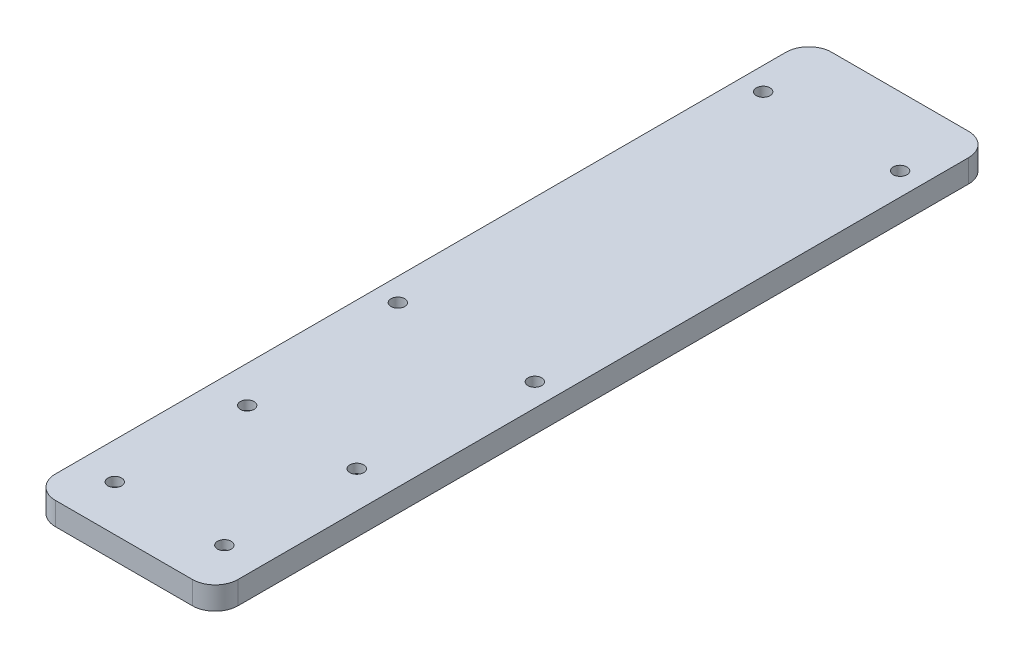
SolidWorks part; units mm, degrees
ref_plane "前视基准面" through (0, 0, 0) normal (0, 0, 1) x (1, 0, 0)
ref_plane "上视基准面" through (0, 0, 0) normal (0, 1, 0) x (1, 0, 0)
ref_plane "右视基准面" through (0, 0, 0) normal (1, 0, 0) x (0, 0, -1)
other "Configuration Table"
sketch "草图1" plane through (0, 0, 0) normal (0, 1, 0) x (1, 0, 0)
  line L0 (0, 0) -> (0, 30) construction
  line L1 (-20, 85) -> (20, 85)
  line L2 (-20, 85) -> (-20, -85)
  line L3 (-20, -85) -> (20, -85)
  line L4 (20, 85) -> (20, -85)
  line L5 (-20, 85) -> (20, -85) construction
  line L6 (-20, -85) -> (20, 85) construction
  line L7 (-15, 70) -> (15, 70) construction
  line L8 (-15, 70) -> (-15, -10) construction
  line L9 (-15, -10) -> (15, -10) construction
  line L10 (15, 70) -> (15, -10) construction
  line L11 (-15, 70) -> (15, -10) construction
  line L12 (-15, -10) -> (15, 70) construction
  line L14 (-12, -46) -> (12, -46) construction
  line L15 (-12, -46) -> (-12, -75) construction
  line L16 (-12, -75) -> (12, -75) construction
  line L17 (12, -46) -> (12, -75) construction
  line L18 (-12, -46) -> (12, -75) construction
  line L19 (-12, -75) -> (12, -46) construction
  circle A0 centre (-15, 70) radius 1.5
  circle A1 centre (15, 70) radius 1.5
  circle A2 centre (15, -10) radius 1.5
  circle A3 centre (-15, -10) radius 1.5
  circle A4 centre (12, -46) radius 1.5
  circle A5 centre (-12, -46) radius 1.5
  circle A6 centre (-12, -75) radius 1.5
  circle A7 centre (12, -75) radius 1.5
  point P0 (0, 0)
  point P5 (0, 30)
  point P11 (0, -60.5)
  dimension "D5" = 3
  dimension "D12" = 3
  dimension "D1" = 170
  dimension "D2" = 40
  dimension "D3" = 80
  dimension "D4" = 30
  dimension "D8" = 15
  dimension "D9" = 24
  dimension "D10" = 29
  dimension "D11" = 10
  dimension "D6" = 2
  dimension "D7" = 2
  dimension "D13" = 2
  dimension "D14" = 2
extrude "凸台-拉伸1" add sketch "草图1" along normal blind 5
fillet "圆角1" radius 5 4 edges at (-20, 2.5, -85) (20, 2.5, -85) (20, 2.5, 85) (-20, 2.5, 85)
sketch "草图2" plane through (0, 0, 0) normal (0, -1, 0) x (1, 0, 0)
  circle A0 centre (-12, 75) radius 3
  circle A1 centre (12, 75) radius 3
  circle A2 centre (12, 46) radius 3
  circle A3 centre (-12, 46) radius 3
  dimension "D1" = 6
  dimension "D2" = 2
  dimension "D3" = 2
extrude "切除-拉伸1" cut sketch "草图2" against normal blind 3
